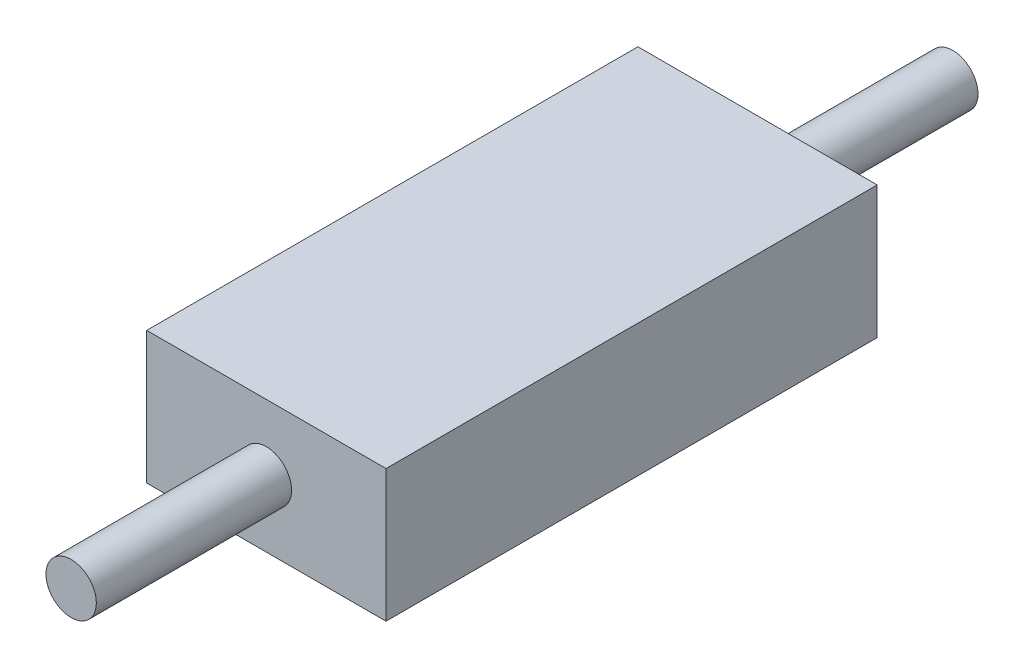
SolidWorks part; units mm, degrees
ref_plane "Front Plane" through (0, 0, 0) normal (0, 0, 1) x (1, 0, 0)
ref_plane "Top Plane" through (0, 0, 0) normal (0, 1, 0) x (1, 0, 0)
ref_plane "Right Plane" through (0, 0, 0) normal (1, 0, 0) x (0, 0, -1)
sketch "Sketch1" plane through (0, 0, 0) normal (0, 0, 1) x (1, 0, 0)
  line L1 (-19, -10.5) -> (19, -10.5)
  line L2 (-19, -10.5) -> (-19, 10.5)
  line L3 (-19, 10.5) -> (19, 10.5)
  line L4 (19, -10.5) -> (19, 10.5)
  line L5 (-19, -10.5) -> (19, 10.5) construction
  line L6 (-19, 10.5) -> (19, -10.5) construction
  point P0 (0, 0)
  dimension "D1" = 38
  dimension "D2" = 21
extrude "Boss-Extrude1" add sketch "Sketch1" along normal blind 78
sketch "Sketch2" plane through (0, 0, 78) normal (0, 0, 1) x (1, 0, 0)
  circle A0 centre (0, 0) radius 4
  dimension "D1" = 8
extrude "Cut-Extrude1" cut sketch "Sketch2" against normal through all
ref_plane "Plane1" through (0, 0, 109) normal (0, 0, 1) x (1, 0, 0)
sketch "Sketch3" plane through (0, 0, 109) normal (0, 0, 1) x (1, 0, 0)
  circle A0 centre (0, 0) radius 4 construction
  circle A1 centre (0, 0) radius 4
extrude "Boss-Extrude2" add sketch "Sketch3" against normal blind 140
